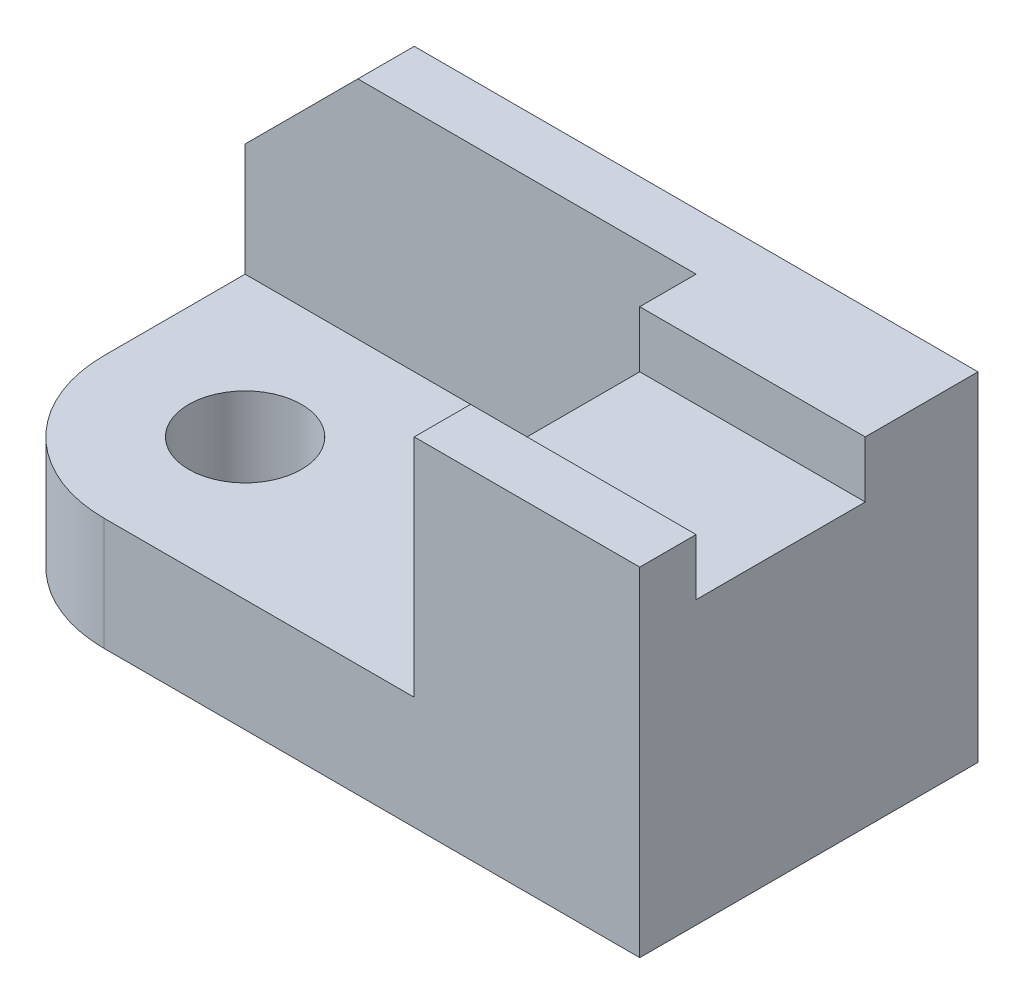
SolidWorks part; units mm, degrees
ref_plane "Front Plane" through (0, 0, 0) normal (0, 0, 1) x (1, 0, 0)
ref_plane "Top Plane" through (0, 0, 0) normal (0, 1, 0) x (1, 0, 0)
ref_plane "Right Plane" through (0, 0, 0) normal (1, 0, 0) x (0, 0, -1)
sketch "Sketch1" plane through (0, 0, 0) normal (0, 1, 0) x (1, 0, 0)
  line L1 (-60, -30) -> (60, -30)
  line L2 (-60, -30) -> (-60, 30)
  line L3 (-60, 30) -> (60, 30)
  line L4 (60, -30) -> (60, 30)
  line L5 (-60, -30) -> (60, 30) construction
  line L6 (-60, 30) -> (60, -30) construction
  point P0 (0, 0)
  dimension "D1" = 120
  dimension "D2" = 60
extrude "Boss-Extrude1" add sketch "Sketch1" along normal blind 20
sketch "Sketch2" plane through (0, 20, 0) normal (0, 1, 0) x (1, 0, 0)
  line L0 (60, -30) -> (60, 30) construction
  line L1 (-60, 30) -> (60, 30)
  line L2 (-60, 30) -> (-60, 20)
  line L3 (-60, 20) -> (60, 20)
  line L4 (60, 30) -> (60, 20)
  dimension "D1" = 10
extrude "Boss-Extrude2" add sketch "Sketch2" along normal blind 40
chamfer "Chamfer1" distance 20 angle 45 1 edges at (-60, 60, -25)
fillet "Fillet1" radius 25 1 edges at (-60, 10, 30)
sketch "Sketch4" plane through (0, 20, 0) normal (0, 1, 0) x (1, 0, 0)
  line L0 (-35, -30) -> (60, -30) construction
  line L1 (60, 20) -> (20, 20)
  line L2 (60, 20) -> (60, -30)
  line L3 (60, -30) -> (20, -30)
  line L4 (20, 20) -> (20, -30)
  dimension "D1" = 40
extrude "Boss-Extrude5" add sketch "Sketch4" along normal up to surface (40 mm away) up to face at (10, 60, -25)
sketch "Sketch5" plane through (0, 60, 0) normal (0, 1, 0) x (1, 0, 0)
  line L0 (20, 20) -> (20, -30) construction
  line L1 (20, 10) -> (60, 10)
  line L2 (20, 10) -> (20, -20)
  line L3 (20, -20) -> (60, -20)
  line L4 (60, 10) -> (60, -20)
  line L5 (60, -30) -> (60, 30) construction
  line L7 (20, -30) -> (60, -30) construction
  dimension "D1" = 30
  dimension "D2" = 10
extrude "Cut-Extrude1" cut sketch "Sketch5" against normal blind 10
sketch "Sketch6" plane through (0, 20, 0) normal (0, 1, 0) x (1, 0, 0)
  circle A0 centre (-35, -5) radius 10
  dimension "D1" = 20
extrude "Cut-Extrude2" cut sketch "Sketch6" against normal through all
